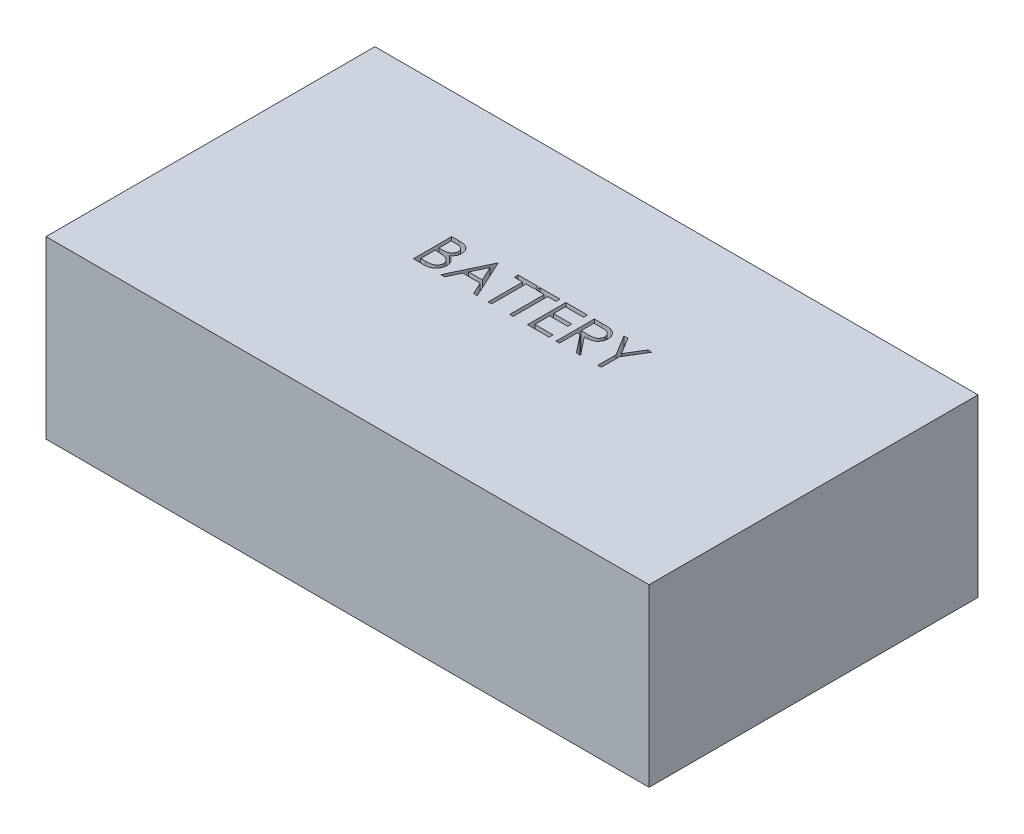
SolidWorks part; units mm, degrees
ref_plane "Front Plane" through (0, 0, 0) normal (0, 0, 1) x (1, 0, 0)
ref_plane "Top Plane" through (0, 0, 0) normal (0, 1, 0) x (1, 0, 0)
ref_plane "Right Plane" through (0, 0, 0) normal (1, 0, 0) x (0, 0, -1)
sketch "Sketch1" plane through (0, 0, 0) normal (0, 1, 0) x (1, 0, 0)
  line L1 (-27.5, -15) -> (27.5, -15)
  line L2 (-27.5, -15) -> (-27.5, 15)
  line L3 (-27.5, 15) -> (27.5, 15)
  line L4 (27.5, -15) -> (27.5, 15)
  line L5 (-27.5, -15) -> (27.5, 15) construction
  line L6 (-27.5, 15) -> (27.5, -15) construction
  point P0 (0, 0)
  dimension "D1" = 55
  dimension "D2" = 30
extrude "Boss-Extrude1" add sketch "Sketch1" along normal blind 16
sketch "Sketch2" plane through (0, 16, 0) normal (0, 1, 0) x (1, 0, 0)
  line L0 (-27.5, 0) -> (27.5, 0) construction
  line L1 (-27.5, 15) -> (-27.5, -15) construction
  line L2 (27.5, -15) -> (27.5, 15) construction
  text T0 "BATTERY"
extrude "Cut-Extrude1" cut sketch "Sketch2" against normal blind 2
